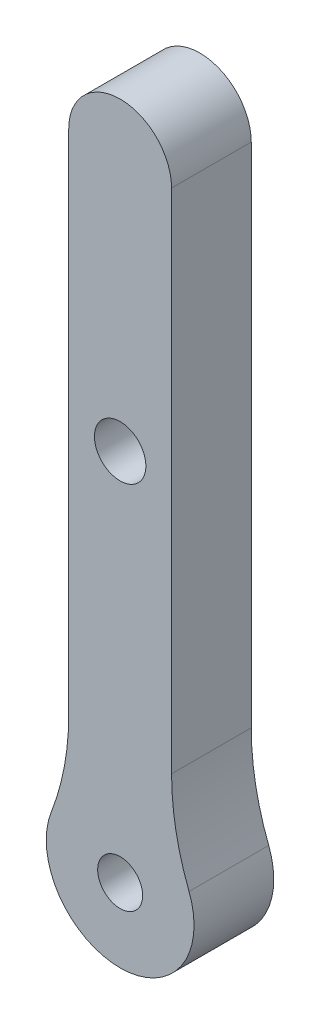
SolidWorks part; units mm, degrees
material "ABS"
ref_plane "Front Plane" through (0, 0, 0) normal (0, 0, 1) x (1, 0, 0)
ref_plane "Top Plane" through (0, 0, 0) normal (0, 1, 0) x (1, 0, 0)
ref_plane "Right Plane" through (0, 0, 0) normal (1, 0, 0) x (0, 0, -1)
sketch "Sketch1" plane through (0, 0, 0) normal (0, 0, 1) x (1, 0, 0)
  line L0 (-32.3584, 33.528) -> (-0.706, 33.528) construction
  line L2 (-9.8806, 13.6966) -> (-9.8806, 34.077) construction
  line L3 (-17.4745, 30.988) -> (10.167, 30.988) construction
  line L4 (-12.4206, 30.988) -> (-12.4206, 14.1091) construction
  line L5 (-7.3406, 30.988) -> (-7.3406, 16.5845) construction
  line L6 (-7.3406, 30.988) -> (-7.3406, 5.925)
  line L7 (-12.4206, 30.988) -> (-12.4206, 5.925)
  circle A0 centre (-9.8806, 0) radius 1.1112
  arc A1 (-13.2837, 1.3231) -> (-6.4775, 1.3231) centre (-9.8806, 0) ccw
  arc A2 (-7.3406, 30.988) -> (-12.4206, 30.988) centre (-9.8806, 30.988) ccw
  arc A3 (-12.4206, 5.925) -> (-13.2837, 1.3231) centre (-25.1206, 5.925) cw
  arc A4 (-7.3406, 5.925) -> (-6.4775, 1.3231) centre (5.3594, 5.925) ccw
  dimension "D1" = 30.988
  dimension "D4" = 12.7
  dimension "D5" = 2.2225
  dimension "D6" = 2.54
  dimension "D2" = 2.54
  dimension "D3" = 2.54
  dimension "D7" = 2.54
extrude "Boss-Extrude1" add sketch "Sketch1" along normal up to surface (3.937 mm away)
sketch "Sketch2" plane through (0, 0, 0) normal (0, 0, -1) x (-1, 0, 0)
  circle A0 centre (9.8806, 18.4565) radius 1.27
  point P2 (0, 0)
  point P3 (0, 0)
  point P4 (0, 0)
  point P5 (0, 0)
  point P6 (9.9221, 18.4565)
  point P7 (9.8363, 18.2279)
  point P8 (9.8806, 18.4565)
  point P9 (0, 0)
  point P10 (9.6648, 18.4565)
  dimension "D1" = 2.54
extrude "Cut-Extrude1" cut sketch "Sketch2" against normal through all
